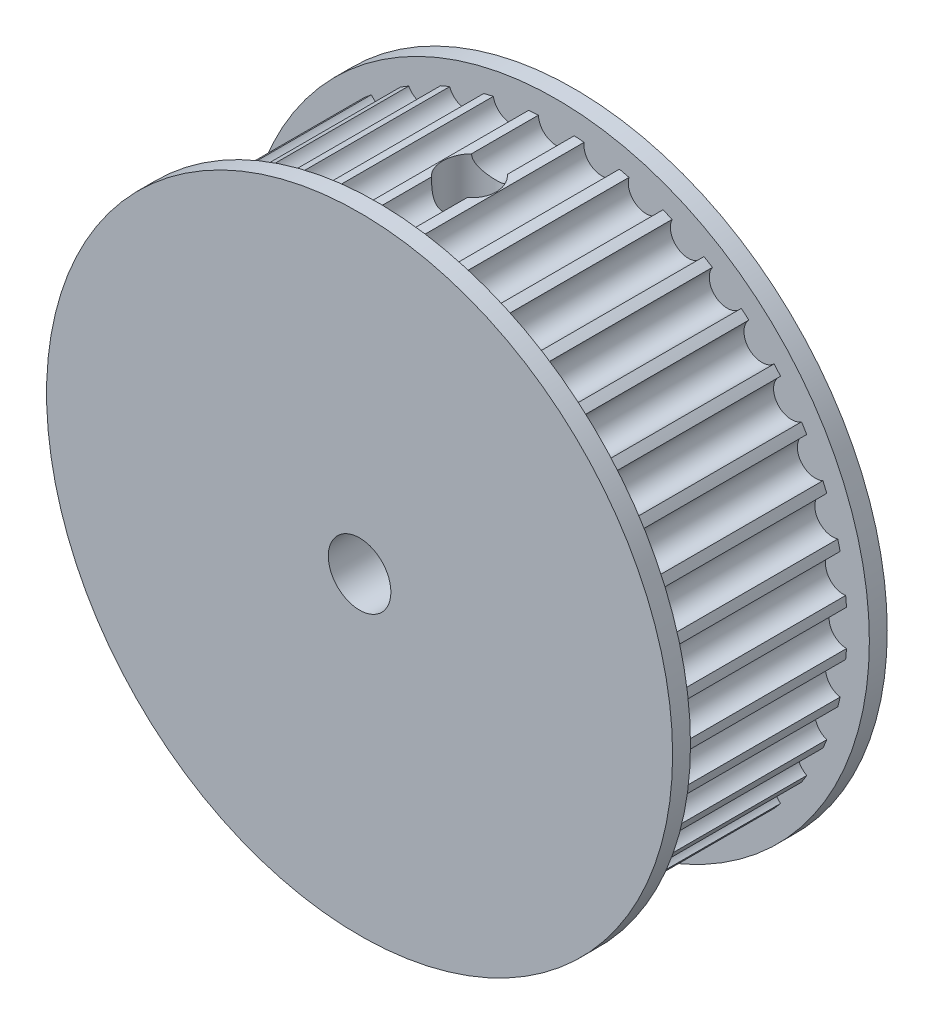
SolidWorks part; units mm, degrees
ref_plane "Front Plane" through (0, 0, 0) normal (0, 0, 1) x (1, 0, 0)
ref_plane "Top Plane" through (0, 0, 0) normal (0, 1, 0) x (1, 0, 0)
ref_plane "Right Plane" through (0, 0, 0) normal (1, 0, 0) x (0, 0, -1)
sketch "Sketch1" plane through (0, 0, 0) normal (0, 0, 1) x (1, 0, 0)
  circle A0 centre (0, 0) radius 35
  circle A1 centre (0, 0) radius 3.5
  dimension "D1" = 70
  dimension "D2" = 7
extrude "Boss-Extrude1" add sketch "Sketch1" against normal blind 24
ref_plane "Plane1" through (0, 0, -2) normal (0, 0, 1) x (1, 0, 0)
sketch "Sketch3" plane through (0, 0, -2) normal (0, 0, 1) x (1, 0, 0)
  circle A0 centre (0, 0) radius 32.5
  dimension "D1" = 65
extrude "Cut-Extrude1" cut sketch "Sketch3" against normal blind 20 flip side to cut
sketch "Sketch4" plane through (0, 0, -2) normal (0, 0, 1) x (1, 0, 0)
  line L0 (0, 0) -> (0, 40.1953) construction
  line L1 (0, -13.2) -> (0, 13.2) construction
  circle A0 centre (0, 0) radius 32.5
  arc A1 (-1.9993, 32.4384) -> (1.9993, 32.4384) centre (0, 32.4926) ccw
  arc A2 (3.0998, 32.3518) -> (7.0491, 31.7263) centre (5.083, 32.0925) ccw
  arc A3 (8.1226, 31.4686) -> (11.9254, 30.233) centre (10.0408, 30.9023) ccw
  arc A4 (12.9454, 29.8105) -> (16.5081, 27.9952) centre (14.7513, 28.9511) ccw
  arc A5 (17.4494, 27.4184) -> (20.6843, 25.0681) centre (19.0987, 26.2871) ccw
  arc A6 (21.5238, 24.3511) -> (24.3511, 21.5238) centre (22.9757, 22.9757) ccw
  arc A7 (25.0681, 20.6843) -> (27.4184, 17.4494) centre (26.2871, 19.0987) ccw
  arc A8 (27.9952, 16.5081) -> (29.8105, 12.9454) centre (28.9511, 14.7513) ccw
  arc A9 (30.233, 11.9254) -> (31.4686, 8.1226) centre (30.9023, 10.0408) ccw
  arc A10 (31.7263, 7.0491) -> (32.3518, 3.0998) centre (32.0925, 5.083) ccw
  arc A11 (32.4384, 1.9993) -> (32.4384, -1.9993) centre (32.4926, 0) ccw
  arc A12 (32.3518, -3.0998) -> (31.7263, -7.0491) centre (32.0925, -5.083) ccw
  arc A13 (31.4686, -8.1226) -> (30.233, -11.9254) centre (30.9023, -10.0408) ccw
  arc A14 (29.8105, -12.9454) -> (27.9952, -16.5081) centre (28.9511, -14.7513) ccw
  arc A15 (27.4184, -17.4494) -> (25.0681, -20.6843) centre (26.2871, -19.0987) ccw
  arc A16 (24.3511, -21.5238) -> (21.5238, -24.3511) centre (22.9757, -22.9757) ccw
  arc A17 (20.6843, -25.0681) -> (17.4494, -27.4184) centre (19.0987, -26.2871) ccw
  arc A18 (16.5081, -27.9952) -> (12.9454, -29.8105) centre (14.7513, -28.9511) ccw
  arc A19 (11.9254, -30.233) -> (8.1226, -31.4686) centre (10.0408, -30.9023) ccw
  arc A20 (7.0491, -31.7263) -> (3.0998, -32.3518) centre (5.083, -32.0925) ccw
  arc A21 (1.9993, -32.4384) -> (-1.9993, -32.4384) centre (0, -32.4926) ccw
  arc A22 (-3.0998, -32.3518) -> (-7.0491, -31.7263) centre (-5.083, -32.0925) ccw
  arc A23 (-8.1226, -31.4686) -> (-11.9254, -30.233) centre (-10.0408, -30.9023) ccw
  arc A24 (-12.9454, -29.8105) -> (-16.5081, -27.9952) centre (-14.7513, -28.9511) ccw
  arc A25 (-17.4494, -27.4184) -> (-20.6843, -25.0681) centre (-19.0987, -26.2871) ccw
  arc A26 (-21.5238, -24.3511) -> (-24.3511, -21.5238) centre (-22.9757, -22.9757) ccw
  arc A27 (-25.0681, -20.6843) -> (-27.4184, -17.4494) centre (-26.2871, -19.0987) ccw
  arc A28 (-27.9952, -16.5081) -> (-29.8105, -12.9454) centre (-28.9511, -14.7513) ccw
  arc A29 (-30.233, -11.9254) -> (-31.4686, -8.1226) centre (-30.9023, -10.0408) ccw
  arc A30 (-31.7263, -7.0491) -> (-32.3518, -3.0998) centre (-32.0925, -5.083) ccw
  arc A31 (-32.4384, -1.9993) -> (-32.4384, 1.9993) centre (-32.4926, 0) ccw
  arc A32 (-32.3518, 3.0998) -> (-31.7263, 7.0491) centre (-32.0925, 5.083) ccw
  arc A33 (-31.4686, 8.1226) -> (-30.233, 11.9254) centre (-30.9023, 10.0408) ccw
  arc A34 (-29.8105, 12.9454) -> (-27.9952, 16.5081) centre (-28.9511, 14.7513) ccw
  arc A35 (-27.4184, 17.4494) -> (-25.0681, 20.6843) centre (-26.2871, 19.0987) ccw
  arc A36 (-24.3511, 21.5238) -> (-21.5238, 24.3511) centre (-22.9757, 22.9757) ccw
  arc A37 (-20.6843, 25.0681) -> (-17.4494, 27.4184) centre (-19.0987, 26.2871) ccw
  arc A38 (-16.5081, 27.9952) -> (-12.9454, 29.8105) centre (-14.7513, 28.9511) ccw
  arc A39 (-11.9254, 30.233) -> (-8.1226, 31.4686) centre (-10.0408, 30.9023) ccw
  arc A40 (-7.0491, 31.7263) -> (-3.0998, 32.3518) centre (-5.083, 32.0925) ccw
  point P129 (0, 0)
  point P225 (0, 0)
  dimension "D1" = 65
  dimension "D2" = 2
  dimension "D3" = 40
extrude "Cut-Extrude2" cut sketch "Sketch4" against normal blind 20 contours A0 A37 | A0 A38 | A0 A39 | A0 A40 | A1 L0 A0 | L0 A1 A0 | A0 A2 | A0 A3 | A0 A4 | A0 A5 | A0 A6 | A0 A7 | A0 A8 | A0 A9 | A0 A10 | A0 A11 | A0 A12 | A0 A13 | A0 A14 | A0 A15 | A0 A16 | A0 A17 | A0 A18 | A0 A19 | A0 A20 | A0 A21 | A0 A22 | A0 A23 | A0 A24 | A0 A25 | A0 A26 | A0 A27 | A0 A28 | A0 A29 | A0 A30 | A0 A31 | A0 A32 | A0 A33 | A0 A34 | A0 A35 | A0 A36
sketch "Sketch5" plane through (0, 0, 0) normal (0, 1, 0) x (1, 0, 0)
  line L0 (0, -13.2) -> (0, 13.2) construction
  circle A0 centre (0, 12.2792) radius 3
  dimension "D1" = 6
extrude "Cut-Extrude3" cut sketch "Sketch5" along normal through all
